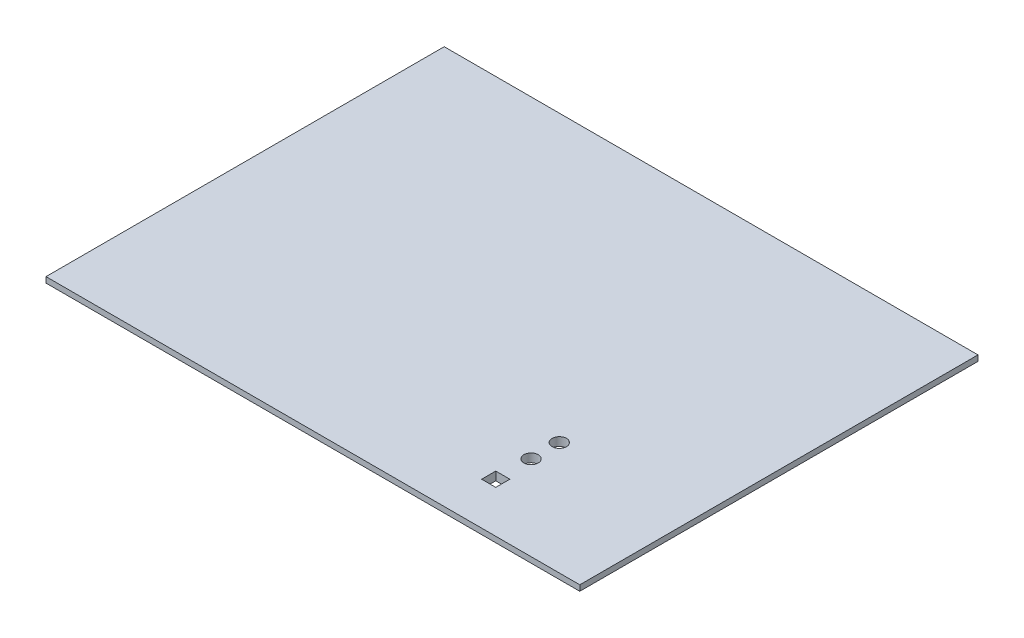
SolidWorks part; units mm, degrees
ref_plane "Plano frontal" through (0, 0, 0) normal (0, 0, 1) x (1, 0, 0)
ref_plane "Plano superior" through (0, 0, 0) normal (0, 1, 0) x (1, 0, 0)
ref_plane "Plano direito" through (0, 0, 0) normal (1, 0, 0) x (0, 0, -1)
sketch "Esboço1" plane through (0, 0, 0) normal (0, 1, 0) x (1, 0, 0)
  line L1 (-89.95, -65.95) -> (89.95, -65.95)
  line L2 (-89.95, -65.95) -> (-89.95, 65.95)
  line L3 (-89.95, 65.95) -> (89.95, 65.95)
  line L4 (89.95, -65.95) -> (89.95, 65.95)
  line L5 (-89.95, -65.95) -> (89.95, 65.95) construction
  line L6 (-89.95, 65.95) -> (89.95, -65.95) construction
  point P0 (0, 0)
  dimension "D1" = 179.9
  dimension "D2" = 131.9
extrude "Ressalto-extrusão1" add sketch "Esboço1" along normal blind 1
sketch "Esboço2" plane through (0, 1, 0) normal (0, 1, 0) x (1, 0, 0)
  line L1 (-94.5, -70.5) -> (94.5, -70.5)
  line L2 (-94.5, -70.5) -> (-94.5, 70.5)
  line L3 (-94.5, 70.5) -> (94.5, 70.5)
  line L4 (94.5, -70.5) -> (94.5, 70.5)
  line L5 (-94.5, -70.5) -> (94.5, 70.5) construction
  line L6 (-94.5, 70.5) -> (94.5, -70.5) construction
  point P0 (0, 0)
  dimension "D1" = 189
  dimension "D2" = 141
extrude "Ressalto-extrusão2" add sketch "Esboço2" along normal blind 2
sketch "Esboço3" plane through (0, 3, 0) normal (0, 1, 0) x (1, 0, 0)
  line L0 (0, 0) -> (0, -70.5) construction
  line L1 (-94.5, -70.5) -> (94.5, -70.5) construction
  line L2 (0, 0) -> (94.5, 0) construction
  line L3 (94.5, -70.5) -> (94.5, 70.5) construction
  line L4 (47.25, 0) -> (47.25, -70.5) construction
  line L5 (47.25, -35.25) -> (94.5, -35.25) construction
  line L7 (44.75, -55.5) -> (49.75, -55.5)
  line L8 (44.75, -55.5) -> (44.75, -50.5)
  line L9 (44.75, -50.5) -> (49.75, -50.5)
  line L10 (49.75, -55.5) -> (49.75, -50.5)
  line L11 (44.75, -55.5) -> (49.75, -50.5) construction
  line L12 (44.75, -50.5) -> (49.75, -55.5) construction
  circle A0 centre (47.25, -40.5) radius 2.55
  circle A1 centre (47.25, -30.5) radius 2.55
  point P16 (47.25, -53)
  point P21 (0, 0)
  point P22 (0, 0)
  point P23 (0, 0)
  point P24 (0, 0)
  point P25 (0, 0)
  dimension "D1" = 5.1
  dimension "D2" = 5
  dimension "D3" = 5
  dimension "D4" = 10
  dimension "D5" = 30
  dimension "D6" = 15
extrude "Corte-extrusão1" cut sketch "Esboço3" against normal through all
